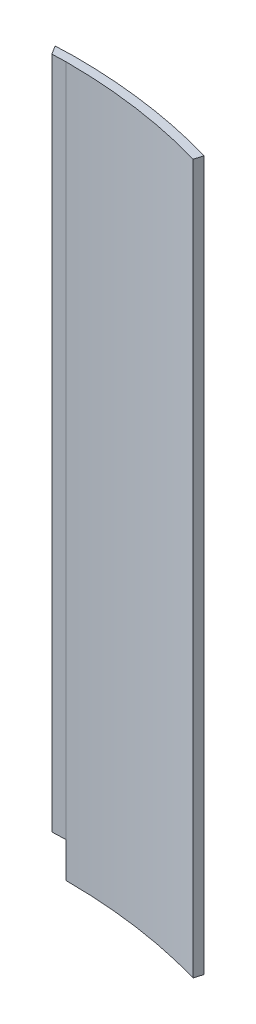
SolidWorks part; units mm, degrees
ref_plane "前视基准面" through (0, 0, 0) normal (0, 0, 1) x (1, 0, 0)
ref_plane "上视基准面" through (0, 0, 0) normal (0, 1, 0) x (1, 0, 0)
ref_plane "右视基准面" through (0, 0, 0) normal (1, 0, 0) x (0, 0, -1)
sketch "草图1" plane through (0, 0, 0) normal (0, 1, 0) x (1, 0, 0)
  line L0 (0, 0) -> (0, 1540) construction
  line L1 (424.4815, 1480.343) -> (0, 0) construction
  line L2 (0, 1540) -> (0, 1515)
  line L3 (424.4815, 1480.343) -> (417.5906, 1456.3115)
  arc A0 (0, 1540) -> (424.4815, 1480.343) centre (0, 0) cw
  arc A1 (0, 1515) -> (417.5906, 1456.3115) centre (0, 0) cw
  dimension "D3" = 1515
  dimension "D1" = 1540
  dimension "D2" = 16
extrude "凸台-拉伸1" add sketch "草图1" along normal blind 2000
sketch "草图2" plane through (0, 2000, 0) normal (0, 1, 0) x (1, 0, 0)
  line L0 (-0.0872, 2.4985) -> (494.3399, 1524.1889) construction
  line L1 (-0.0872, 2.4985) -> (494.3399, 1524.1889)
  line L2 (424.4815, 1480.343) -> (475.5963, 1463.7348)
  line L3 (417.5906, 1456.3115) -> (467.0624, 1440.2371)
  line L4 (214.3266, 1525.0128) -> (210.8472, 1500.2561) construction
  line L5 (475.5963, 1463.7348) -> (454.1566, 1444.4305)
  line L6 (417.5906, 1456.3115) -> (424.4815, 1480.343)
  line L7 (0, 1515) -> (0, 1540)
  line L8 (-53.7125, 1538.1243) -> (-38.4244, 1513.6582)
  line L9 (0, 1515) -> (-51.986, 1513.1846)
  line L10 (0, 1540) -> (-53.7125, 1538.1243)
  line L11 (-40.4645, 1516.9231) -> (-53.7125, 1538.1243) construction
  arc A0 (424.4815, 1480.343) -> (0, 1540) centre (0, 0) ccw construction
  arc A1 (417.5906, 1456.3115) -> (0, 1515) centre (0, 0) ccw construction
  line M6 (0, 1540) -> (0, 1515)
  dimension "D1" = 60
extrude "凸台-拉伸2" add sketch "草图2" against normal up to surface (1900 mm away) contours L10 L8 L9 M6
